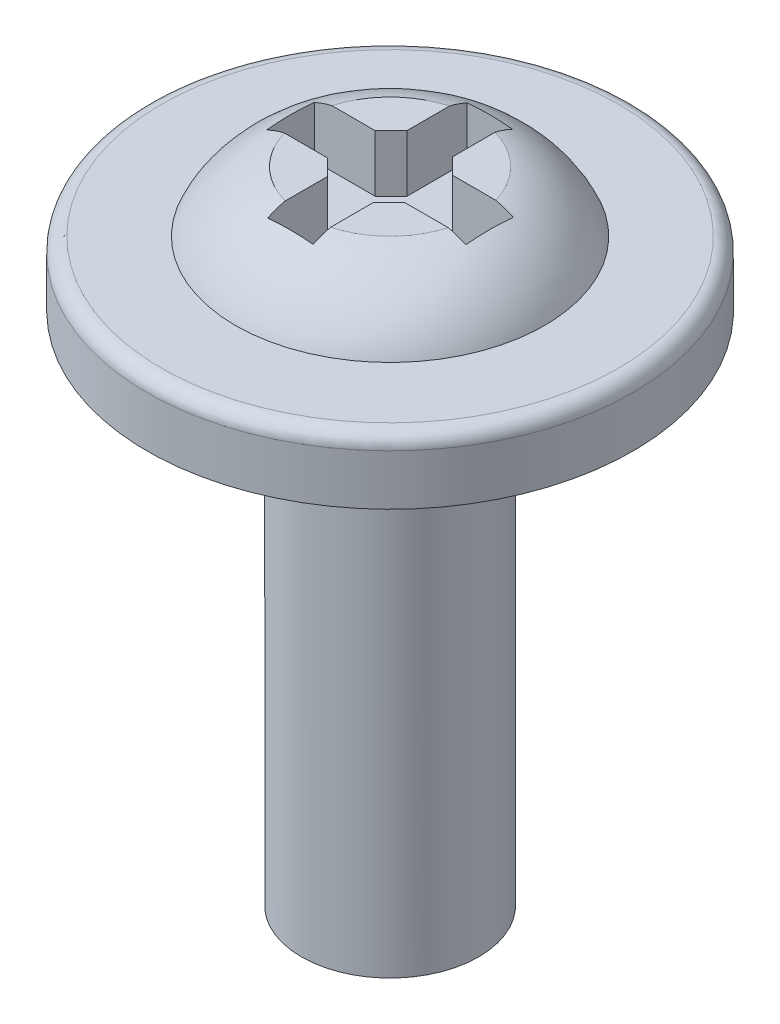
SolidWorks part; units mm, degrees
ref_plane "Front Plane" through (0, 0, 0) normal (0, 0, 1) x (1, 0, 0)
ref_plane "Top Plane" through (0, 0, 0) normal (0, 1, 0) x (1, 0, 0)
ref_plane "Right Plane" through (0, 0, 0) normal (1, 0, 0) x (0, 0, -1)
sketch "Sketch2" plane through (0, 0, 0) normal (1, 0, 0) x (0, 0, -1)
  line L0 (0, 6.35) -> (5.4229, 6.35)
  line L1 (0, 9.144) -> (0, 6.35)
  line L2 (0, 7.7978) -> (3.4544, 7.7978)
  line L3 (0, 9.144) -> (1.905, 9.144)
  line L4 (5.4229, 6.35) -> (5.4229, 7.7978)
  line L5 (3.4544, 7.7978) -> (5.4229, 7.7978)
  line L6 (0, 0) -> (1.9812, 0)
  line L7 (1.9812, 0) -> (1.9812, 6.35)
  line L8 (0, 0) -> (0, 25.8053) construction
  line L9 (0, 0) -> (0, -6.35)
  line L10 (0, 6.35) -> (0, 0)
  line L11 (1.9812, 0) -> (1.9812, -5.1526)
  line L12 (1.9812, -5.1526) -> (0, -6.35)
  spline S0 degree 3 poles (1.905, 9.144) (2.4859, 9.0132) (3.1698, 8.4818) (3.4544, 7.7978) knots 0 0 0 0 1 1 1 1
  dimension "D7" = 1.9812
  dimension "D1" = 5.4229
  dimension "D2" = 3.4544
  dimension "D3" = 1.4478
  dimension "D4" = 1.905
  dimension "D5" = 2.794
  dimension "D6" = 6.35
  dimension "D8" = 12.7
revolve "Revolve2" add sketch "Sketch2" angle 360 about L8
sketch "Sketch4" plane through (0, 9.144, 0) normal (0, 1, 0) x (1, 0, 0)
  line L0 (-0.508, 2.2288) -> (0.508, 2.2288)
  line L1 (-0.508, 2.2288) -> (-0.508, 0.8846)
  line L2 (-0.508, -2.2288) -> (0.508, -2.2288)
  line L3 (0.508, -2.2288) -> (0.508, -0.8846)
  line L4 (-2.2236, 0.5306) -> (-2.2236, -0.5306)
  line L5 (-2.2236, 0.5306) -> (-0.862, 0.5306)
  line L6 (2.2236, 0.5306) -> (2.2236, -0.5306)
  line L7 (2.2236, -0.5306) -> (0.862, -0.5306)
  line L8 (0.508, 0.8846) -> (0.862, 0.5306)
  line L9 (0.862, -0.5306) -> (0.508, -0.8846)
  line L10 (-0.508, -0.8846) -> (-0.862, -0.5306)
  line L11 (-0.862, 0.5306) -> (-0.508, 0.8846)
  line L12 (-0.508, -0.8846) -> (-0.508, -2.2288)
  line L13 (0.862, 0.5306) -> (2.2236, 0.5306)
  line L14 (0.508, 0.8846) -> (0.508, 2.2288)
  line L15 (-0.862, -0.5306) -> (-2.2236, -0.5306)
  circle A0 centre (0, 0) radius 2.286
  dimension "D1" = 4.572
  dimension "D2" = 1.016
extrude "Cut-Extrude1" cut sketch "Sketch4" against normal blind 1.27
fillet "Fillet1" radius 0.3175 1 edges at (0, 7.7978, -5.4229)
